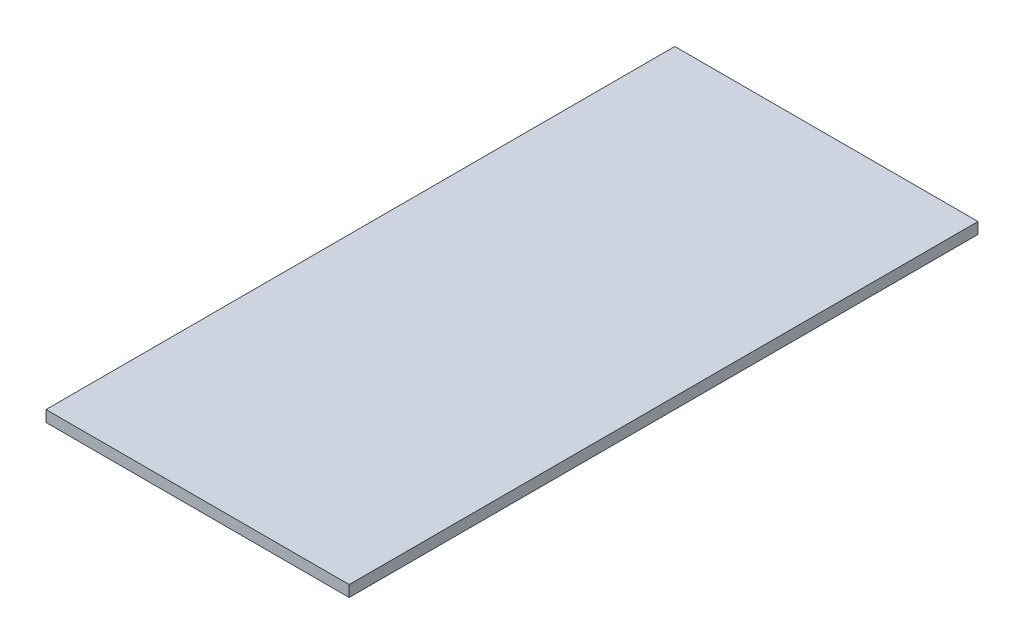
SolidWorks part; units mm, degrees
material "Pine"
ref_plane "Front Plane" through (0, 0, 0) normal (0, 0, 1) x (1, 0, 0)
ref_plane "Top Plane" through (0, 0, 0) normal (0, 1, 0) x (1, 0, 0)
ref_plane "Right Plane" through (0, 0, 0) normal (1, 0, 0) x (0, 0, -1)
sketch3d "6deg Playfield Gradient" [suppressed]
  line L0 (-257.175, 0, 0) -> (257.175, 0, 0)
  line L1 (257.175, 0, 0) -> (257.175, 111.511, -1060.956)
  line L2 (-257.175, 0, 0) -> (-257.175, 111.511, -1060.956)
  line L3 (-257.175, 111.511, -1060.956) -> (257.175, 111.511, -1060.956)
  line L4 (257.175, 0, 0) -> (257.175, 0, -1060.956) construction
  line L5 (257.175, 0, -1060.956) -> (257.175, 111.511, -1060.956) construction
  line L6 (-257.175, 111.511, -1060.956) -> (-257.175, 0, -1060.956) construction
  line L7 (-257.175, 0, -1060.956) -> (-257.175, 0, 0) construction
  line L8 (257.175, 0, -1060.956) -> (-257.175, 0, -1060.956) construction
  line L9 (257.175, 55.7555, -530.478) -> (257.175, 0, -536.3381) construction
  point P4 (0, 0, 0)
  dimension "D1" = 514.35
  dimension "D2" = 6
  dimension "D3" = 1066.8
ref_plane "Plane2" [suppressed] through (0, 0, 0) normal (0, -0.9945, -0.1045) x (-1, 0, 0)
sketch "Sketch2" [suppressed] plane through (0, 0, 0) normal (0, 1, 0) x (-1, 0, 0)
  line L0 (257.175, 0) -> (-257.175, 0) construction
  line L1 (-257.175, 0) -> (-257.175, -1060.956) construction
  line L2 (257.175, -1060.956) -> (-257.175, -1060.956) construction
  line L3 (257.175, 0) -> (257.175, -1060.956) construction
  line L4 (257.175, 0) -> (-257.175, 0)
  line L5 (-257.175, 0) -> (-257.175, -1060.956)
  line L6 (257.175, -1060.956) -> (-257.175, -1060.956)
  line L7 (257.175, 0) -> (257.175, -1060.956)
extrude "Boss-Extrude2" [suppressed] add sketch "Sketch2" against normal blind 19.05
sketch "Sketch3" plane through (0, 0, 0) normal (0, 1, 0) x (1, 0, 0)
  line L1 (-257.175, -533.4) -> (257.175, -533.4)
  line L2 (-257.175, -533.4) -> (-257.175, 533.4)
  line L3 (-257.175, 533.4) -> (257.175, 533.4)
  line L4 (257.175, -533.4) -> (257.175, 533.4)
  line L5 (-257.175, -533.4) -> (257.175, 533.4) construction
  line L6 (-257.175, 533.4) -> (257.175, -533.4) construction
  point P0 (0, 0)
  dimension "D1" = 514.35
  dimension "D2" = 1066.8
extrude "Boss-Extrude3" add sketch "Sketch3" along normal blind 19.05
equation "\"Gradient\"= 8"
